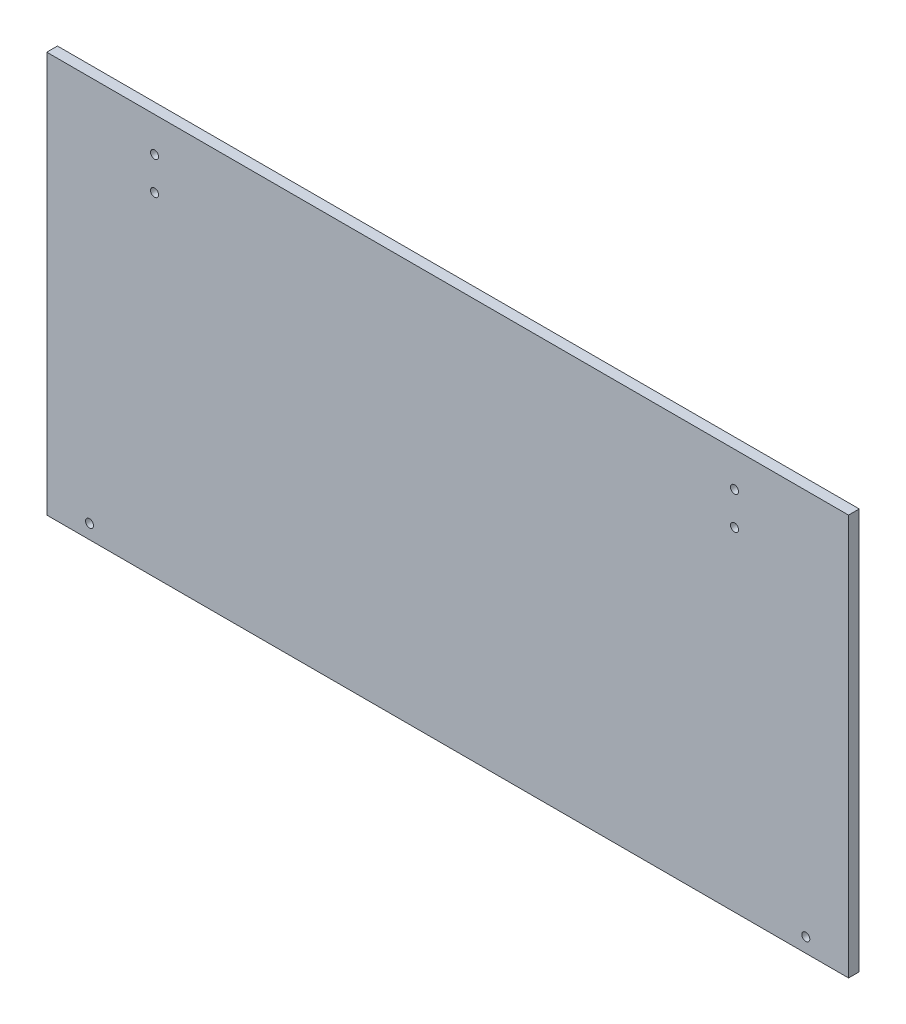
SolidWorks part; units mm, degrees
material "Pino"
ref_plane "Piano frontale" through (0, 0, 0) normal (0, 0, 1) x (1, 0, 0)
ref_plane "Piano superiore" through (0, 0, 0) normal (0, 1, 0) x (1, 0, 0)
ref_plane "Piano destro" through (0, 0, 0) normal (1, 0, 0) x (0, 0, -1)
sketch "Schizzo1" plane through (0, 0, 0) normal (0, 0, 1) x (1, 0, 0)
  line L5 (-225, 112.5) -> (225, 112.5)
  line L6 (-225, 112.5) -> (-225, -112.5)
  line L7 (-225, -112.5) -> (225, -112.5)
  line L8 (225, 112.5) -> (225, -112.5)
  line L9 (-225, 112.5) -> (225, -112.5) construction
  line L10 (-225, -112.5) -> (225, 112.5) construction
  point P8 (0, 0)
  dimension "D1" = 225
  dimension "D2" = 450
extrude "Estrusione-Estrusione1" add sketch "Schizzo1" along normal blind 6
sketch "Schizzo2" plane through (0, 0, 6) normal (0, 0, 1) x (1, 0, 0)
  circle A0 centre (-164.5, 93) radius 2.25
  circle A1 centre (-164.5, 74.5) radius 2.25
  circle A2 centre (161, 93) radius 2.25
  circle A3 centre (161, 74.5) radius 2.25
  dimension "D1" = 4.5
extrude "Taglio-Estrusione1" cut sketch "Schizzo2" against normal blind 10
sketch "Schizzo3" plane through (0, 0, 6) normal (0, 0, 1) x (1, 0, 0)
  line L0 (-225, 112.5) -> (-225, -112.5) construction
  line L1 (-225, -112.5) -> (225, -112.5) construction
  line L2 (-201, -104.5) -> (201, -104.5) construction
  line L3 (225, -112.5) -> (225, 112.5) construction
  circle A0 centre (-201, -104.5) radius 2.25
  circle A1 centre (201, -104.5) radius 2.25
  dimension "D1" = 4.5
  dimension "D4" = 24
  dimension "D2" = 24
  dimension "D3" = 8
extrude "Taglio-Estrusione2" cut sketch "Schizzo3" against normal blind 10
